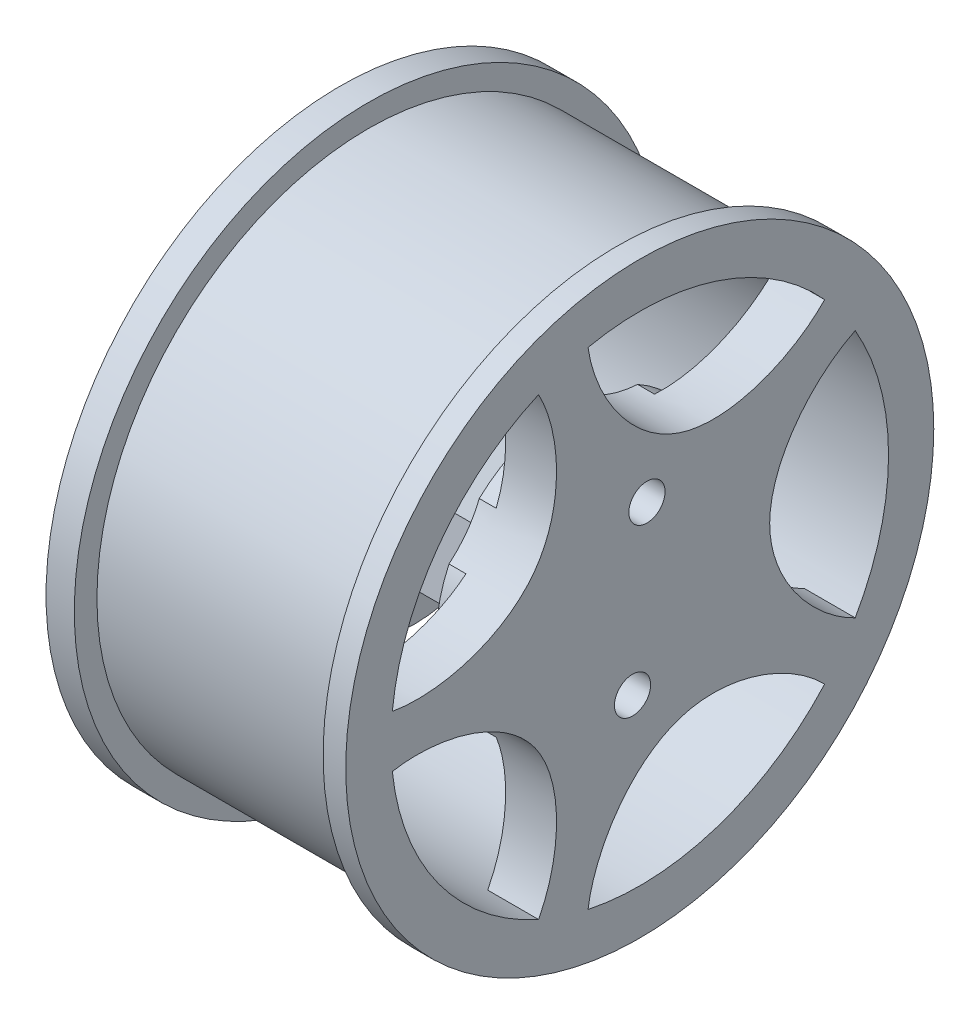
SolidWorks part; units mm, degrees
ref_plane "정면" through (0, 0, 0) normal (0, 0, 1) x (1, 0, 0)
ref_plane "윗면" through (0, 0, 0) normal (0, 1, 0) x (1, 0, 0)
ref_plane "우측면" through (0, 0, 0) normal (1, 0, 0) x (0, 0, -1)
sketch "Sketch2" plane through (0, 0, 0) normal (1, 0, 0) x (0, 0, -1)
  circle A0 centre (-65.6774, 69.6681) radius 10.75
  circle A1 centre (-65.0401, 76.7394) radius 1.6
  circle A2 centre (-61.8032, 76.4477) radius 0.5
  circle A3 centre (-58.3144, 72.2677) radius 0.5
  circle A4 centre (-58.6061, 69.0308) radius 0.5
  circle A5 centre (-58.8978, 65.7939) radius 0.5
  circle A6 centre (-63.0778, 62.305) radius 0.5
  circle A7 centre (-69.5516, 62.8885) radius 0.5
  circle A8 centre (-73.0405, 67.0685) radius 0.5
  circle A9 centre (-72.7488, 70.3054) radius 0.5
  circle A10 centre (-72.457, 73.5423) radius 0.5
  circle A11 centre (-68.277, 77.0312) radius 0.5
  circle A12 centre (-66.3147, 62.5968) radius 1.6
sketch "Sketch3" plane through (0, 0, 0) normal (1, 0, 0) x (0, 0, -1)
  circle A0 centre (-65.6774, 69.6681) radius 26
  dimension "D1" = 52
extrude "Boss-Extrude1" add sketch "Sketch3" against normal blind 26.5 contours A0
sketch "Sketch4" plane through (0, 0, 0) normal (1, 0, 0) x (0, 0, -1)
  circle A0 centre (-65.6774, 69.6681) radius 24
ref_plane "Plane1" through (-2, 0, 0) normal (1, 0, 0) x (0, 0, -1)
sketch "Sketch5" plane through (-2, 0, 0) normal (1, 0, 0) x (0, 0, -1)
  circle A0 centre (-65.6774, 69.6681) radius 24 construction
  circle A1 centre (-65.6774, 69.6681) radius 24
  circle A2 centre (-65.6774, 69.6681) radius 26
  dimension "D1" = 52
extrude "Cut-Extrude1" cut sketch "Sketch5" against normal blind 22
extrude "Cut-Extrude2" cut sketch "Sketch2" against normal through all contours A1 | A12
sketch "Sketch6" plane through (0, 0, 0) normal (1, 0, 0) x (0, 0, -1)
  arc A0 (-74.6256, 89.7661) -> (-87.5569, 71.9677) centre (-65.6774, 69.6681) ccw
  arc A1 (-49.3282, 84.389) -> (-70.2515, 91.1874) centre (-65.6774, 69.6681) ccw
  arc A2 (-46.6249, 58.6681) -> (-46.6249, 80.6681) centre (-65.6774, 69.6681) ccw
  arc A3 (-70.2515, 48.1489) -> (-49.3282, 54.9472) centre (-65.6774, 69.6681) ccw
  arc A4 (-87.5569, 67.3685) -> (-74.6256, 49.5701) centre (-65.6774, 69.6681) ccw
  spline S0 degree 3 poles (-46.6249, 80.6681) (-50.5057, 78.7763) (-57.8697, 69.6681) (-50.5057, 60.5599) (-46.6249, 58.6681) knots 0 0 0 0 0.5 1 1 1 1
  spline S1 degree 3 poles (-49.3282, 54.9472) (-52.3267, 58.0536) (-63.2647, 62.2425) (-69.6515, 52.4244) (-70.2515, 48.1489) knots 0 0 0 0 0.5 1 1 1 1
  spline S2 degree 3 poles (-74.6256, 49.5701) (-72.5979, 53.3818) (-71.994, 65.0788) (-83.3052, 68.1191) (-87.5569, 67.3685) knots 0 0 0 0 0.5 1 1 1 1
  spline S3 degree 3 poles (-87.5569, 71.9677) (-83.3052, 71.2171) (-71.994, 74.2574) (-72.5979, 85.9544) (-74.6256, 89.7661) knots 0 0 0 0 0.5 1 1 1 1
  spline S4 degree 3 poles (-70.2515, 91.1874) (-69.6515, 86.9118) (-63.2647, 77.0937) (-52.3267, 81.2827) (-49.3282, 84.389) knots 0 0 0 0 0.5 1 1 1 1
  point P35 (-65.6774, 69.6681)
extrude "Cut-Extrude3" cut sketch "Sketch6" against normal blind 17
ref_plane "Plane2" through (-6, 0, 0) normal (1, 0, 0) x (0, 0, -1)
sketch "Sketch8" plane through (-6, 0, 0) normal (1, 0, 0) x (0, 0, -1)
  circle A0 centre (-65.6774, 69.6681) radius 22
extrude "Cut-Extrude6" cut sketch "Sketch8" against normal blind 14
sketch "Sketch9" plane through (0, 0, 0) normal (1, 0, 0) x (0, 0, -1)
  circle A0 centre (-65.6774, 69.6681) radius 12
sketch "Sketch10" plane through (-26.5, 0, 0) normal (-1, 0, 0) x (0, 0, 1)
  circle A0 centre (65.6774, 69.6681) radius 12
  circle A1 centre (65.6774, 69.6681) radius 22
  dimension "D1" = 44
extrude "Cut-Extrude8" cut sketch "Sketch10" against normal blind 22
sketch "Sketch11" plane through (-26.5, 0, 0) normal (-1, 0, 0) x (0, 0, 1)
  line L0 (65.0401, 76.7394) -> (66.3147, 62.5968) construction
  line L1 (53.7259, 68.591) -> (77.629, 70.7452) construction
  circle A0 centre (65.6774, 69.6681) radius 12 construction
  circle A1 centre (53.7259, 68.591) radius 9
  circle A2 centre (77.629, 70.7452) radius 9
  point P7 (65.6774, 69.6681)
extrude "Cut-Extrude9" cut sketch "Sketch11" against normal blind 7
sketch "Sketch12" plane through (-26.5, 0, 0) normal (-1, 0, 0) x (0, 0, 1)
  line L0 (65.0401, 76.7394) -> (66.3147, 62.5968) construction
  line L1 (57.7563, 68.9542) -> (73.5985, 70.382) construction
  line L2 (59.3875, 72.6154) -> (71.339, 73.6925)
  line L3 (71.339, 73.6925) -> (71.9674, 66.7208)
  line L4 (71.9674, 66.7208) -> (60.0158, 65.6437)
  line L5 (60.0158, 65.6437) -> (59.3875, 72.6154)
  point P6 (65.6774, 69.6681)
  dimension "D1" = 3.5
  dimension "D2" = 3.5
  dimension "D3" = 6
  dimension "D4" = 6
extrude "Boss-Extrude2" add sketch "Sketch12" against normal through all
sketch "Sketch13" plane through (-26.5, 0, 0) normal (-1, 0, 0) x (0, 0, 1)
  circle A0 centre (65.6774, 69.6681) radius 12
extrude "Cut-Extrude10" cut sketch "Sketch13" against normal blind 2 contours A0
